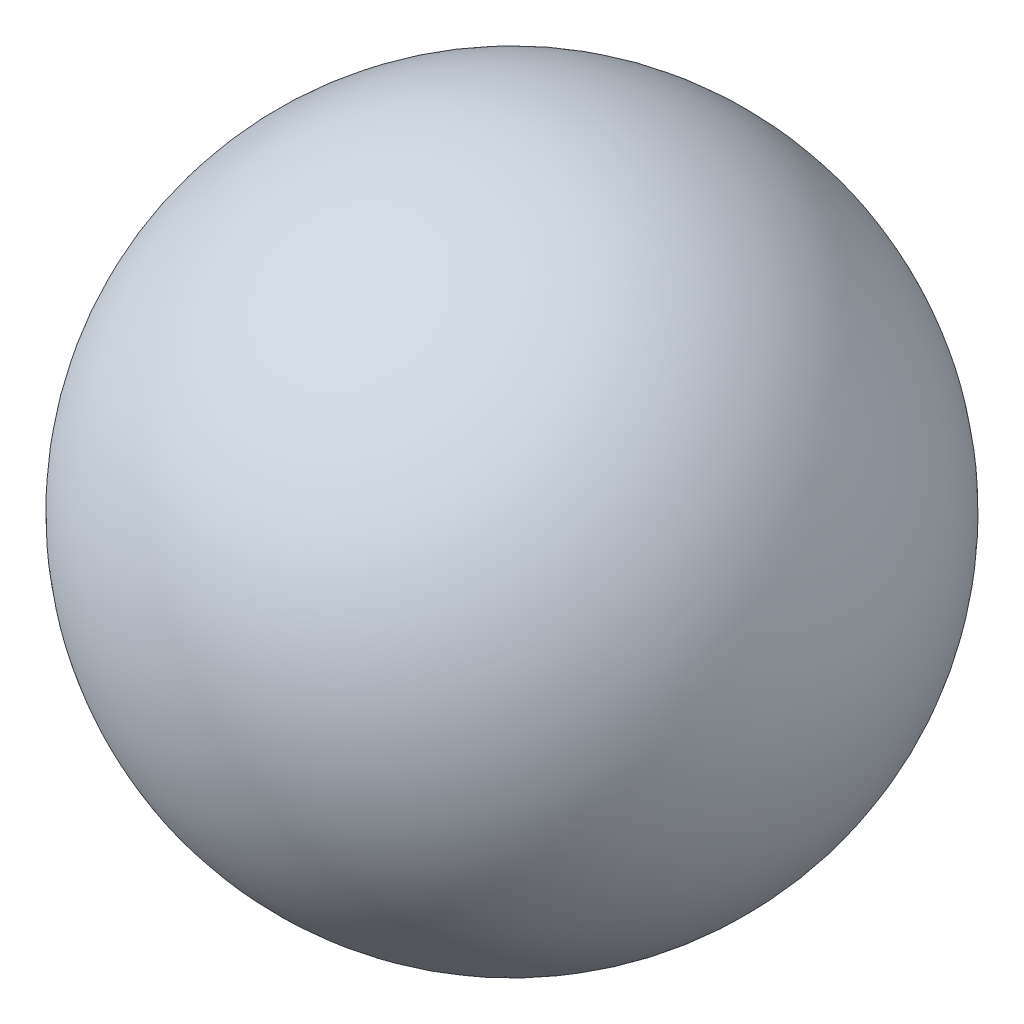
SolidWorks part; units mm, degrees
ref_plane "Front Plane" through (0, 0, 0) normal (0, 0, 1) x (1, 0, 0)
ref_plane "Top Plane" through (0, 0, 0) normal (0, 1, 0) x (1, 0, 0)
ref_plane "Right Plane" through (0, 0, 0) normal (1, 0, 0) x (0, 0, -1)
sketch "Sketch1" plane through (0, 0, 0) normal (0, 1, 0) x (1, 0, 0)
  line L0 (0, 54.852) -> (0, -58.1349) construction
  line L1 (0, 7.874) -> (0, -7.874)
  arc A0 (0, -7.874) -> (0, 7.874) centre (0, 0) ccw
  dimension "D1" = 7.874
revolve "Revolve1" add sketch "Sketch1" angle 360 about L0
